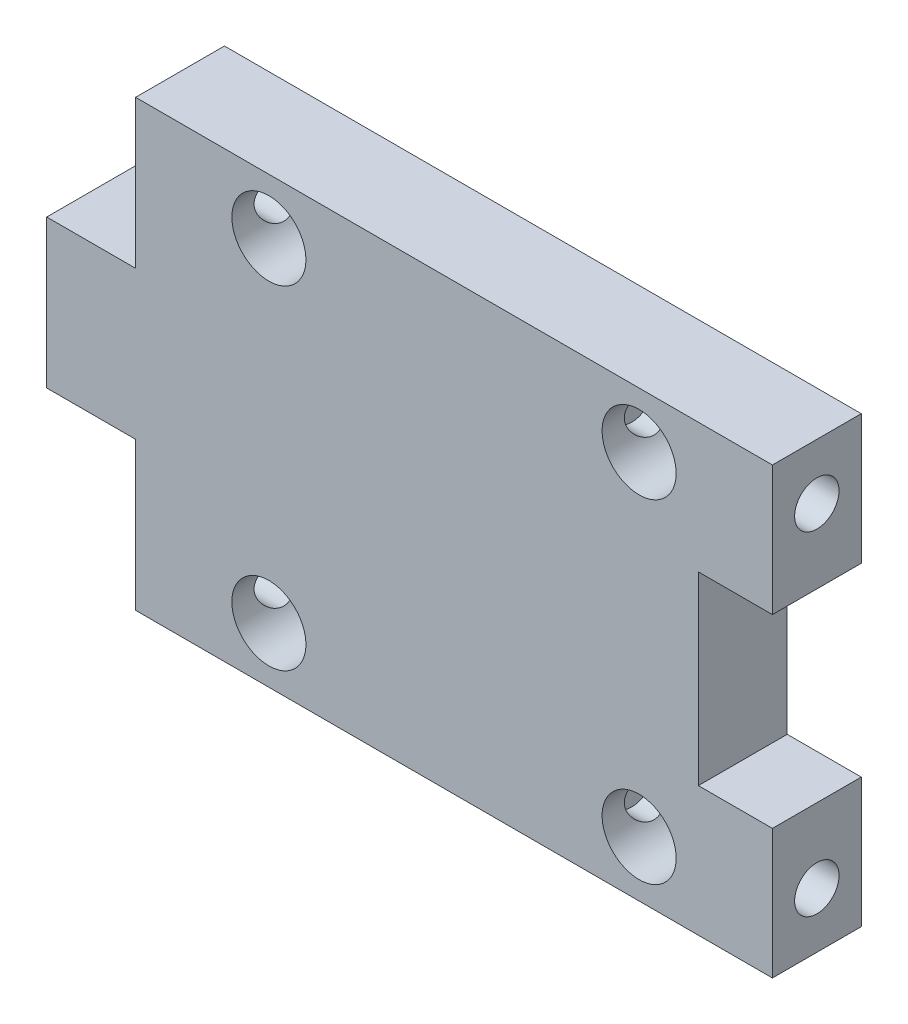
SolidWorks part; units mm, degrees
material "HDPE-green"
ref_plane "Front Plane" through (0, 0, 0) normal (0, 0, 1) x (1, 0, 0)
ref_plane "Top Plane" through (0, 0, 0) normal (0, 1, 0) x (1, 0, 0)
ref_plane "Right Plane" through (0, 0, 0) normal (1, 0, 0) x (0, 0, -1)
sketch "Sketch1" plane through (0, 0, 0) normal (0, 0, 1) x (1, 0, 0)
  line L1 (0, 0) -> (86, 0)
  line L2 (0, 0) -> (0, 60)
  line L3 (0, 60) -> (86, 60)
  line L4 (86, 0) -> (86, 60)
  dimension "D1" = 86
  dimension "D2" = 60
extrude "Boss-Extrude1" add sketch "Sketch1" along normal blind 12
sketch "Sketch2" plane through (0, 0, 12) normal (0, 0, 1) x (1, 0, 0)
  line L0 (86, 0) -> (86, 60) construction
  line L1 (96, 17.5) -> (76, 17.5)
  line L2 (96, 17.5) -> (96, 42.5)
  line L3 (96, 42.5) -> (76, 42.5)
  line L4 (76, 17.5) -> (76, 42.5)
  line L5 (96, 17.5) -> (76, 42.5) construction
  line L6 (96, 42.5) -> (76, 17.5) construction
  point P0 (86, 30)
  dimension "D1" = 25
  dimension "D2" = 20
extrude "Cut-Extrude1" cut sketch "Sketch2" against normal up to next
sketch "Sketch3" plane through (0, 0, 12) normal (0, 0, 1) x (1, 0, 0)
  line L0 (0, 60) -> (0, 0) construction
  line L1 (12, 20) -> (-12, 20)
  line L2 (12, 20) -> (12, 40)
  line L3 (12, 40) -> (-12, 40)
  line L4 (-12, 20) -> (-12, 40)
  line L5 (12, 20) -> (-12, 40) construction
  line L6 (12, 40) -> (-12, 20) construction
  point P0 (0, 30)
  dimension "D1" = 24
  dimension "D2" = 20
extrude "Boss-Extrude2" add sketch "Sketch3" against normal blind 12
sketch "Sketch4" plane through (0, 0, 12) normal (0, 0, 1) x (1, 0, 0)
  line L0 (89.5686, 52.5) -> (42.9559, 52.5) construction
  line L1 (42.9559, 7.5) -> (89.5686, 7.5) construction
  line L2 (76, 42.5) -> (76, 17.5) construction
  line L4 (86, 42.5) -> (86, 60) construction
  line L5 (86, 0) -> (86, 17.5) construction
  circle A1 centre (68, 52.5) radius 5
  circle A2 centre (68, 7.5) radius 5
  point P4 (76, 30)
  dimension "D3" = 10
  dimension "D4" = 10
  dimension "D7" = 18
  dimension "D8" = 18
  dimension "D1" = 45
  dimension "D2" = 22.5
extrude "Cut-Extrude2" cut sketch "Sketch4" against normal up to next
sketch "Sketch5" plane through (86, 0, 0) normal (1, 0, 0) x (0, 0, -1)
  line L0 (-12, 52.5) -> (0, 52.5) construction
  line L1 (-12, 42.5) -> (-12, 60) construction
  line L2 (0, 42.5) -> (0, 60) construction
  line L3 (-12, 7.5) -> (0, 7.5) construction
  line L4 (-12, 0) -> (-12, 17.5) construction
  line L5 (0, 0) -> (0, 17.5) construction
  line L6 (-12, 42.5) -> (-12, 17.5) construction
  line L7 (-6, 60) -> (-6, 0) construction
  line L8 (-12, 60) -> (0, 60) construction
  line L9 (-12, 0) -> (0, 0) construction
  circle A0 centre (-6, 52.5) radius 3
  circle A1 centre (-6, 7.5) radius 3
  point P12 (-12, 30)
  dimension "D3" = 6
  dimension "D4" = 6
  dimension "D1" = 45
  dimension "D2" = 22.5
extrude "Cut-Extrude3" cut sketch "Sketch5" against normal blind 25
ref_plane "Plane3" through (43, 0, 0) normal (-1, 0, 0) x (0, 0, 1)
mirror "Mirror2" about plane through (43, 0, 0) normal (-1, 0, 0) of "Cut-Extrude3", "Cut-Extrude2"
